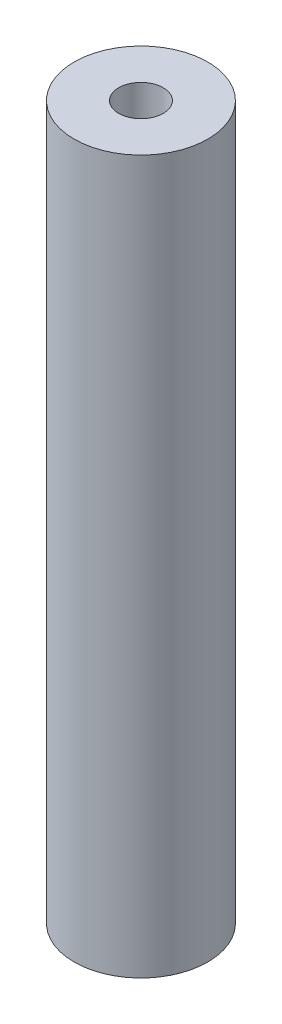
SolidWorks part; units mm, degrees
material "1060 Alloy"
ref_plane "Front Plane" through (0, 0, 0) normal (0, 0, 1) x (1, 0, 0)
ref_plane "Top Plane" through (0, 0, 0) normal (0, 1, 0) x (1, 0, 0)
ref_plane "Right Plane" through (0, 0, 0) normal (1, 0, 0) x (0, 0, -1)
sketch "Sketch1" plane through (0, 0, 0) normal (0, 1, 0) x (1, 0, 0)
  circle A0 centre (0, 0) radius 2.5
  circle A1 centre (0, 0) radius 7.5
  dimension "D1" = 5
  dimension "D2" = 15
extrude "Boss-Extrude1" add sketch "Sketch1" along normal blind 80
